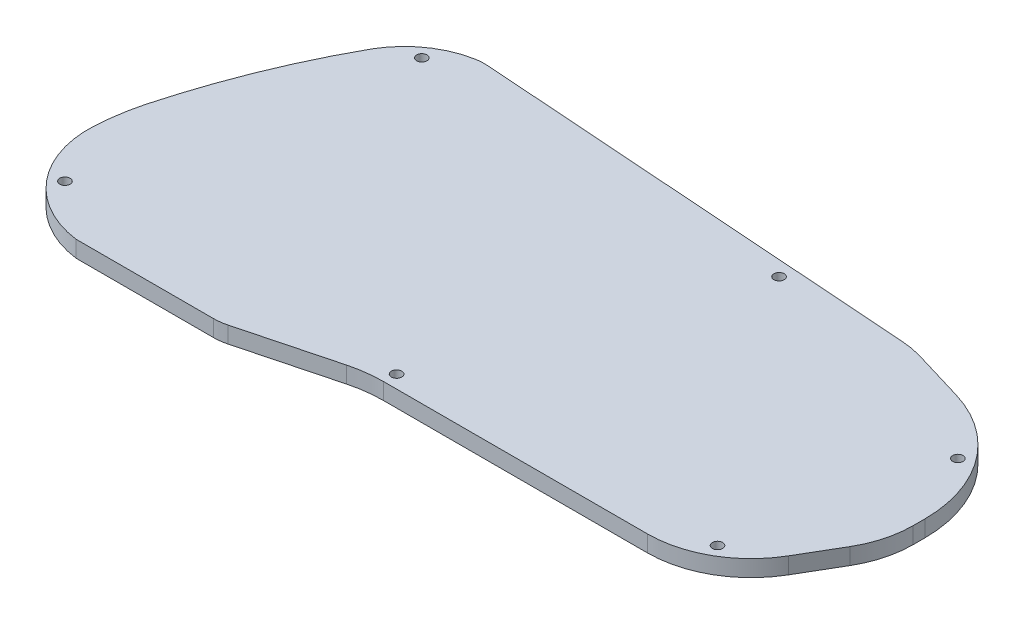
SolidWorks part; units mm, degrees
ref_plane "Front Plane" through (0, 0, 0) normal (0, 0, 1) x (1, 0, 0)
ref_plane "Top Plane" through (0, 0, 0) normal (0, 1, 0) x (1, 0, 0)
ref_plane "Right Plane" through (0, 0, 0) normal (1, 0, 0) x (0, 0, -1)
sketch "Sketch2" plane through (0, 0, 0) normal (0, 1, 0) x (1, 0, 0)
  line L0 (-179.3866, -46.5771) -> (-152.974, -46.5771)
  line L1 (-150.4402, -46.2508) -> (-132.3693, -41.5176)
  line L2 (-126.0349, -40.7018) -> (-75.2281, -40.7018)
  line L3 (-57.9662, -30.8028) -> (-53.582, -23.3104)
  line L4 (-50.9807, -13.7145) -> (-50.9807, -11.4807)
  line L5 (-68.6114, 12.2079) -> (-77.2874, 14.8078)
  line L6 (-82.8699, 15.9614) -> (-168.5856, 22.0343)
  circle A0 centre (-66.5223, -35.8827) radius 1
  circle A1 centre (-57.8777, 1.7914) radius 1
  circle A2 centre (-105.4336, 14.8895) radius 1
  arc A3 (-152.974, -46.5771) -> (-150.4402, -46.2508) centre (-152.974, -36.5771) ccw
  arc A4 (-126.0349, -40.7018) -> (-132.3693, -41.5176) centre (-126.0349, -65.7018) ccw
  arc A5 (-75.2281, -40.7018) -> (-57.9662, -30.8028) centre (-75.2281, -20.7018) ccw
  arc A6 (-53.582, -23.3104) -> (-50.9807, -13.7145) centre (-69.9807, -13.7145) ccw
  arc A7 (-50.9807, -11.4807) -> (-68.6114, 12.2079) centre (-75.7101, -11.4807) ccw
  arc A8 (-168.5856, 22.0343) -> (-171.2206, 21.8717) centre (-169.2923, 12.0593) ccw
  arc A9 (-171.2206, 21.8717) -> (-182.65, 13.7167) centre (-167.9425, 5.1907) ccw
  arc A10 (-195.2335, -17.4525) -> (-196.5482, -25.9134) centre (-152.3075, -28.4555) ccw
  arc A11 (-196.5482, -25.9134) -> (-179.3866, -46.5771) centre (-176.8875, -27.0432) ccw
  circle A12 centre (-176.3645, 16.9942) radius 1
  circle A13 centre (-190.1608, -37.971) radius 1
  circle A14 centre (-126.0349, -38.2018) radius 1
  spline S0 degree 2 poles (-77.2874, 14.8078) (-78.6029, 15.2606) (-80.4963, 15.6624) (-81.3306, 15.7967) (-81.9124, 15.8724) (-82.2021, 15.9031) (-82.5583, 15.9394) (-82.8699, 15.9614) knots 0.680418 0.680418 0.680418 0.836668 0.899168 0.935139 0.961668 0.966389 1 1 1
  spline S1 degree 3 poles (-182.65, 13.7167) (-184.0202, 11.2666) (-186.5955, 6.271) (-189.9737, -1.4423) (-192.8775, -9.3673) (-194.4957, -14.744) (-195.2335, -17.4525) knots 0.255799 0.255799 0.255799 0.255799 0.41293 0.570061 0.727192 0.884323 0.884323 0.884323 0.884323
extrude "Boss-Extrude1" add sketch "Sketch2" along normal blind 3.175
